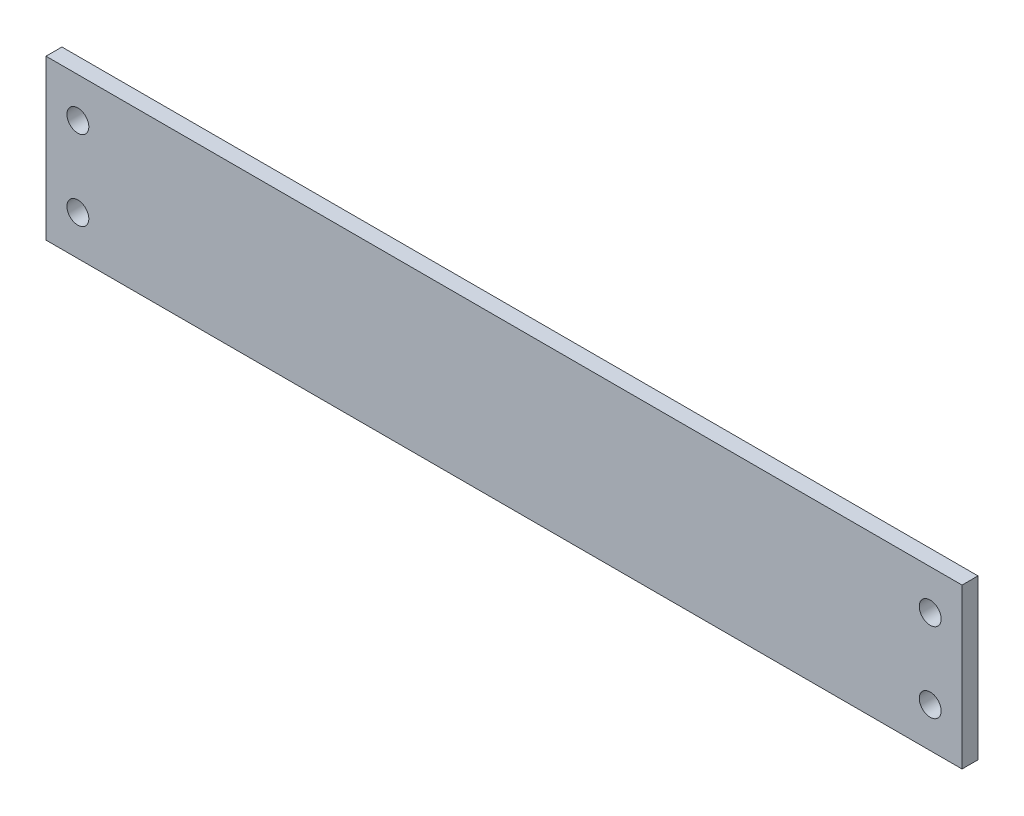
SolidWorks part; units mm, degrees
ref_plane "Front Plane" through (0, 0, 0) normal (0, 0, 1) x (1, 0, 0)
ref_plane "Top Plane" through (0, 0, 0) normal (0, 1, 0) x (1, 0, 0)
ref_plane "Right Plane" through (0, 0, 0) normal (1, 0, 0) x (0, 0, -1)
sketch "Extrusion Base Sketch" plane through (0, 0, 0) normal (0, 0, 1) x (1, 0, 0)
  line L0 (208.75, 36.75) -> (208.75, -3.25)
  line L1 (0, 0) -> (187.5, 0) construction
  line L2 (0, 0) -> (0, 33.5) construction
  line L3 (0, 33.5) -> (187.5, 33.5) construction
  line L4 (187.5, 0) -> (187.5, 33.5) construction
  line L5 (-21.25, 36.75) -> (208.75, 36.75)
  line L6 (-3.25, 36.75) -> (-3.25, -3.25) construction
  line L7 (-21.25, -3.25) -> (208.75, -3.25)
  line L8 (190.75, 36.75) -> (190.75, -3.25) construction
  line L9 (-21.25, 36.75) -> (-21.25, -3.25)
  line L10 (200.75, 26.75) -> (200.75, 6.75) construction
  line L11 (200.75, 16.75) -> (208.75, 16.75) construction
  line L12 (-13.25, 26.75) -> (-13.25, 6.75) construction
  line L13 (-13.25, 16.75) -> (-21.25, 16.75) construction
  dimension "D1" = 33.5
  dimension "D2" = 187.5
  dimension "D4" = 3.25
  dimension "D5" = 3.25
  dimension "D6" = 3.25
  dimension "D3" = 40
  dimension "D7" = 230
extrude "Extrusion Base Extrude" add sketch "Extrusion Base Sketch" against normal blind 4
hole_wizard "M5 Mounting Holes" positions "M5 Mounting Holes Position Sketch" profile "M5 Mounting Holes Profile Sketch" hole size "M5" standard "ANSI Metric" end condition through all
sketch "M5 Mounting Holes Position Sketch" plane through (0, 0, -4) normal (0, 0, -1) x (-1, 0, 0)
  point P0 (-200.75, 26.75)
  point P2 (-200.75, 6.75)
  point P4 (13.25, 26.75)
  point P6 (13.25, 6.75)
sketch "M5 Mounting Holes Profile Sketch" plane through (200.75, 26.75, -4) normal (1, 0, 0) x (0, 1, 0)
  line L0 (0, 0) -> (0, 4)
  line L1 (0, 4) -> (2.75, 4)
  line L2 (2.75, 4) -> (2.75, 0)
  line L5 (2.75, 0) -> (0, 0)
  line L11 (0, -6.35) -> (0, 107.95) construction
  dimension "Thru Hole Dia." = 5.5
  dimension "Thru Hole Depth" = 4
equation "\"Logo Height\"= 33.5mm"
equation "\"Total Height\"= 40mm"
equation "\"Border\"= ( \"Total Height\" - \"Logo Height\" ) / 2"
equation "\"Logo Length\"= 187.5mm"
equation "\"D1@Extrusion Base Sketch\" = \"Logo Height\""
equation "\"D2@Extrusion Base Sketch\" = \"Logo Length\""
equation "\"D4@Extrusion Base Sketch\" = \"Border\""
equation "\"D5@Extrusion Base Sketch\" = \"Border\""
equation "\"D6@Extrusion Base Sketch\" = \"Border\""
equation "\"D3@Extrusion Base Sketch\" = \"Total Height\""
